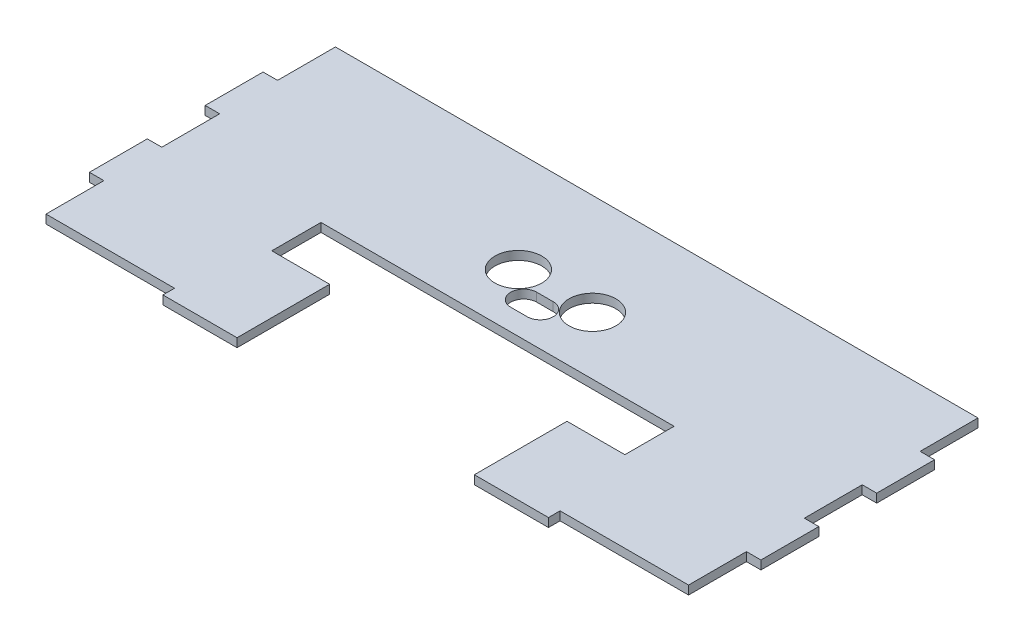
SolidWorks part; units mm, degrees
ref_plane "Front Plane" through (0, 0, 0) normal (0, 0, 1) x (1, 0, 0)
ref_plane "Top Plane" through (0, 0, 0) normal (0, 1, 0) x (1, 0, 0)
ref_plane "Right Plane" through (0, 0, 0) normal (1, 0, 0) x (0, 0, -1)
sketch "Sketch1" plane through (0, 0, 0) normal (0, 1, 0) x (1, 0, 0)
  line L0 (-111, 30) -> (-116, 30)
  line L1 (-111, -50) -> (-66.6, -50)
  line L2 (-111, -50) -> (-111, -30)
  line L3 (-111, 50) -> (111, 50)
  line L4 (111, -50) -> (111, -30)
  line L5 (-111, -50) -> (-41, -18.4685) construction
  line L6 (-111, 50) -> (11.1, -5) construction
  line L7 (-116, 30) -> (-116, 10)
  line L8 (-116, 10) -> (-111, 10)
  line L9 (0, 50) -> (0, 27.6) construction
  line L10 (-111, -10) -> (-116, -10)
  line L11 (-116, -10) -> (-116, -30)
  line L12 (-116, -30) -> (-111, -30)
  line L13 (-111, 30) -> (-111, 50)
  line L14 (-111, -10) -> (-111, 10)
  line L15 (116, -30) -> (111, -30)
  line L16 (116, -10) -> (116, -30)
  line L17 (111, -10) -> (116, -10)
  line L18 (116, 10) -> (111, 10)
  line L19 (116, 30) -> (116, 10)
  line L20 (111, 30) -> (116, 30)
  line L21 (111, 30) -> (111, 50)
  line L22 (111, -10) -> (111, 10)
  line L24 (-66.6, -54) -> (-41, -54)
  line L25 (-66.6, -54) -> (-66.6, -50)
  line L29 (66.6, -54) -> (66.6, -50)
  line L30 (41, -54) -> (66.6, -54)
  line L31 (66.6, -50) -> (111, -50)
  line L32 (-12.8, 15) -> (12.8, 15) construction
  line L35 (0, 18.6) -> (0, -5) construction
  line L36 (-2.85, 2.4) -> (2.85, 2.4)
  line L37 (-2.85, 11.4) -> (2.85, 11.4)
  line L38 (-11.1, -5) -> (111, 50) construction
  line L40 (-41, -54) -> (-41, -22)
  line L41 (-41, -5) -> (41, -5)
  line L42 (41, -54) -> (41, -22)
  line L43 (-41, -5) -> (-61, -5)
  line L45 (22.2, -54) -> (22.2, -50) [skipped]
  line L46 (41, -18.4685) -> (111, -50) construction
  line L48 (41, -5) -> (61, -5)
  line L51 (-61, -5) -> (-61, -22)
  line L52 (-61, -22) -> (-41, -22)
  line L53 (61, -5) -> (61, -22)
  line L54 (61, -22) -> (41, -22)
  circle A0 centre (12.8, 15) radius 8.1
  circle A1 centre (-12.8, 15) radius 8.1
  arc A4 (2.85, 11.4) -> (2.85, 2.4) centre (2.85, 6.9) cw
  arc A5 (-2.85, 2.4) -> (-2.85, 11.4) centre (-2.85, 6.9) cw
  point P0 (0, 0)
  dimension "D14" = 16.2
  dimension "D15" = 16.2
  dimension "D17" = 17
  dimension "D18" = 17
  dimension "D16" = 82
  dimension "D1" = 222
  dimension "D2" = 100
  dimension "D3" = 20
  dimension "D4" = 20
  dimension "D5" = 5
  dimension "D7" = 20
  dimension "D8" = 2
  dimension "D9" = 44.4
  dimension "D10" = 4
  dimension "D11" = 12.8
  dimension "D12" = 12.8
  dimension "D13" = 20
  dimension "D6" = 2
extrude "Boss-Extrude1" add sketch "Sketch1" along normal blind 3
